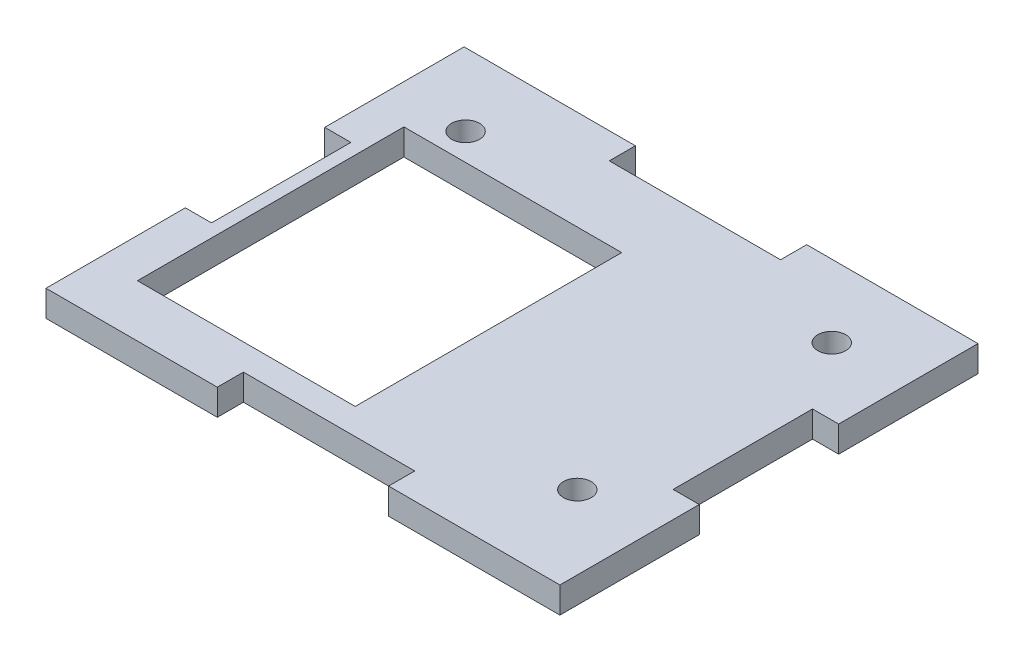
SolidWorks part; units mm, degrees
ref_plane "Front Plane" through (0, 0, 0) normal (0, 0, 1) x (1, 0, 0)
ref_plane "Top Plane" through (0, 0, 0) normal (0, 1, 0) x (1, 0, 0)
ref_plane "Right Plane" through (0, 0, 0) normal (1, 0, 0) x (0, 0, -1)
sketch "Sketch1" plane through (0, 0, 0) normal (0, 1, 0) x (1, 0, 0)
  line L0 (-29.5, 24) -> (-29.5, 8)
  line L1 (-25, -19.5) -> (25, -19.5) construction
  line L2 (-25, -19.5) -> (-25, 19.5) construction
  line L3 (-25, 19.5) -> (25, 19.5) construction
  line L4 (25, -19.5) -> (25, 19.5) construction
  line L5 (-25, -19.5) -> (25, 19.5) construction
  line L6 (-25, 19.5) -> (25, -19.5) construction
  line L11 (-29.5, 8) -> (-26.5, 8)
  line L12 (-26.5, 8) -> (-26.5, -8)
  line L13 (-26.5, -8) -> (-29.5, -8)
  line L14 (-29.5, -8) -> (-29.5, -24)
  line L15 (-29.5, -24) -> (-9.8333, -24)
  line L16 (-9.8333, -24) -> (-9.8333, -21)
  line L17 (-9.8333, -21) -> (9.8333, -21)
  line L18 (9.8333, -21) -> (9.8333, -24)
  line L19 (9.8333, -24) -> (29.5, -24)
  line L20 (-21.0185, 15.69) -> (0, 0) construction
  line L21 (29.5, -24) -> (29.5, -8)
  line L22 (29.5, -8) -> (26.5, -8)
  line L23 (26.5, -8) -> (26.5, 8)
  line L24 (26.5, 8) -> (29.5, 8)
  line L25 (29.5, 8) -> (29.5, 24)
  line L26 (29.5, 24) -> (9.8333, 24)
  line L27 (9.8333, 24) -> (9.8333, 21)
  line L28 (9.8333, 21) -> (-9.8333, 21)
  line L29 (-9.8333, 21) -> (-9.8333, 24)
  line L30 (-9.8333, 24) -> (-29.5, 24)
  line L31 (0, 0) -> (21.0185, 15.69) construction
  circle A0 centre (-21.0185, 15.69) radius 1.6
  circle A1 centre (21.0185, 15.69) radius 1.6
  circle A2 centre (21.0185, -13.52) radius 1.6
  point P0 (0, 0)
  point P6 (0, 0)
  point P23 (-26.5, 0)
  point P26 (0, -21)
  dimension "D8" = 3.2
  dimension "D1" = 50
  dimension "D2" = 39
  dimension "D3" = 3
  dimension "D4" = 4.5
  dimension "D5" = 4.5
  dimension "D7" = 42.037
  dimension "D9" = 3.81
  dimension "D10" = 29.21
  dimension "D6" = 2
extrude "Boss-Extrude1" add sketch "Sketch1" along normal blind 3
sketch "Sketch2" plane through (0, 3, 0) normal (0, 1, 0) x (1, 0, 0)
  line L0 (9.8333, 21) -> (-9.8333, 21) construction
  line L1 (-25, -18) -> (0, -18)
  line L2 (-25, -18) -> (-25, 12.59)
  line L3 (-25, 12.59) -> (0, 12.59)
  line L4 (0, -18) -> (0, 12.59)
  line L5 (-25, -18) -> (0, 12.59) construction
  line L6 (-25, 12.59) -> (0, -18) construction
  circle A0 centre (-21.0185, 15.69) radius 1.6 construction
  point P0 (-12.5, -2.705)
  point P5 (0, 0)
  point P9 (0, 21)
  dimension "D1" = 1.5
  dimension "D2" = 3
  dimension "D3" = 3.1
extrude "Cut-Extrude1" cut sketch "Sketch2" against normal through all
